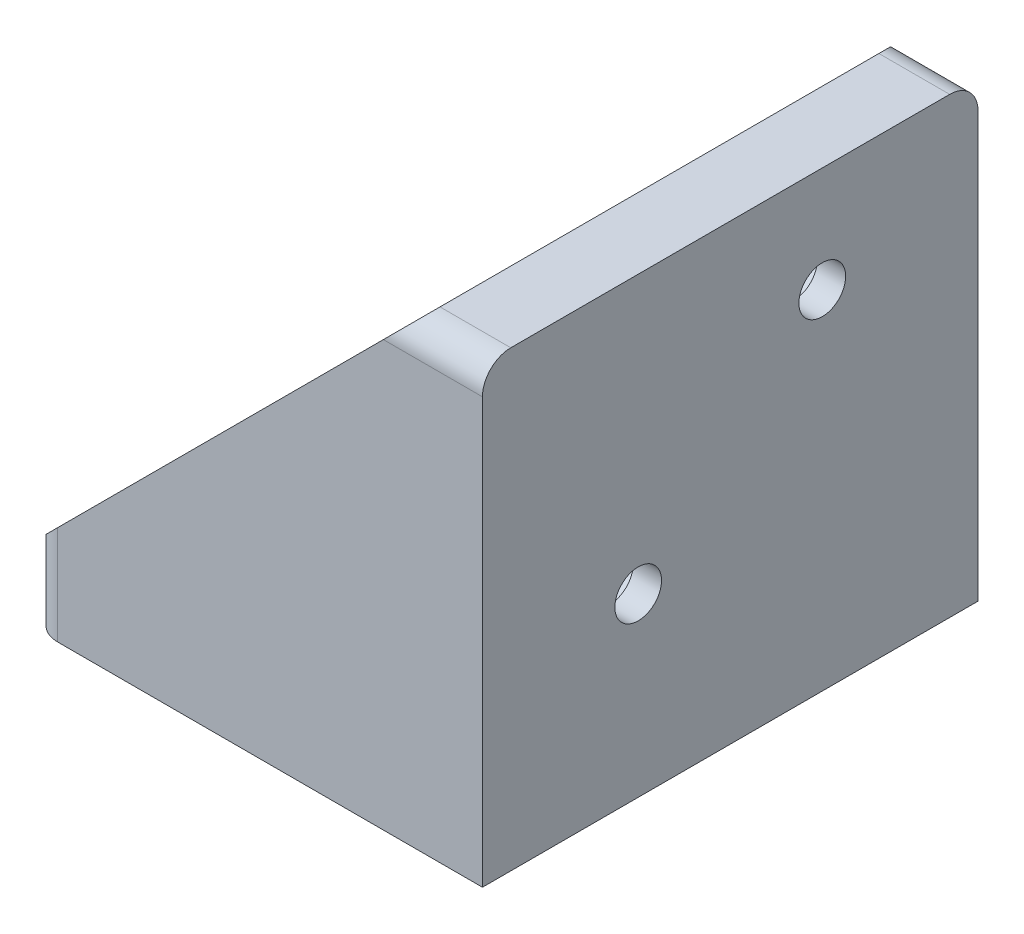
SolidWorks part; units mm, degrees
ref_plane "Спереди" through (0, 0, 0) normal (0, 0, 1) x (1, 0, 0)
ref_plane "Сверху" through (0, 0, 0) normal (0, 1, 0) x (1, 0, 0)
ref_plane "Справа" through (0, 0, 0) normal (1, 0, 0) x (0, 0, -1)
sketch "Эскиз1" plane through (0, 0, 0) normal (0, 0, 1) x (1, 0, 0)
  line L0 (0, 0) -> (-32, 0)
  line L1 (-32, 0) -> (-32, 5)
  line L2 (-32, 5) -> (-5, 5)
  line L3 (-5, 5) -> (-5, 32)
  line L4 (-5, 32) -> (0, 32)
  line L5 (0, 32) -> (0, 0)
  dimension "D1" = 32
  dimension "D2" = 32
  dimension "D3" = 5
  dimension "D4" = 5
extrude "Бобышка-Вытянуть1" add sketch "Эскиз1" along normal blind 35
sketch "Эскиз3" plane through (0, 0, 35) normal (0, 0, 1) x (1, 0, 0)
  line L0 (-32, 5) -> (-5, 32)
rib "Ребро1" sketch "Эскиз3" sketch "Эскиз3" thickness 3 extrusion direction parallel to sketch draft on no parameters "D1"=3
ref_plane "Плоскость4" through (0, 0, 17.5) normal (0, 0, 1) x (1, 0, 0)
mirror "Зеркальное отражение1" about plane through (0, 0, 17.5) normal (0, 0, 1) of "Ребро1"
sketch "Эскиз5" plane through (-5, 0, 0) normal (-1, 0, 0) x (0, 0, 1)
  line L0 (32, 5) -> (3, 32) construction
  line L1 (32, 32) -> (32, 5) construction
  line L2 (24, 8.9842) -> (27, 10.7162)
  line L3 (27, 10.7162) -> (27, 14.1803)
  line L4 (27, 14.1803) -> (24, 15.9124)
  line L5 (24, 15.9124) -> (21, 14.1803)
  line L6 (21, 14.1803) -> (21, 10.7162)
  line L7 (21, 10.7162) -> (24, 8.9842)
  line L8 (3, 5) -> (3, 32) construction
  line L9 (11, 21.0876) -> (14, 22.8197)
  line L10 (14, 22.8197) -> (14, 26.2838)
  line L11 (14, 26.2838) -> (11, 28.0158)
  line L12 (11, 28.0158) -> (8, 26.2838)
  line L13 (8, 26.2838) -> (8, 22.8197)
  line L14 (8, 22.8197) -> (11, 21.0876)
  circle A0 centre (24, 12.4483) radius 3 construction
  circle A1 centre (11, 24.5517) radius 3 construction
  dimension "D1" = 6
  dimension "D2" = 8
  dimension "D3" = 8
extrude "Вырез-Вытянуть1" cut sketch "Эскиз5" against normal blind 3
sketch "Эскиз6" plane through (-2, 0, 0) normal (-1, 0, 0) x (0, 0, 1)
  circle A0 centre (11, 24.5517) radius 3.4641 construction
  circle A1 centre (11, 24.5517) radius 1.65
  circle A2 centre (24, 12.4483) radius 3.4641 construction
  circle A3 centre (24, 12.4483) radius 1.65
  dimension "D1" = 3.3
extrude "Вырез-Вытянуть2" cut sketch "Эскиз6" against normal blind 8
sketch "Эскиз7" plane through (0, 5, 0) normal (0, 1, 0) x (1, 0, 0)
  line L0 (-32, -32) -> (-5, -3) construction
  line L1 (-5, -32) -> (-32, -32) construction
  line L2 (-24.5517, -20.5359) -> (-27.5517, -22.2679)
  line L3 (-27.5517, -22.2679) -> (-27.5517, -25.7321)
  line L4 (-27.5517, -25.7321) -> (-24.5517, -27.4641)
  line L5 (-24.5517, -27.4641) -> (-21.5517, -25.7321)
  line L6 (-21.5517, -25.7321) -> (-21.5517, -22.2679)
  line L7 (-21.5517, -22.2679) -> (-24.5517, -20.5359)
  line L8 (-12.4483, -7.5359) -> (-15.4483, -9.2679)
  line L9 (-15.4483, -9.2679) -> (-15.4483, -12.7321)
  line L10 (-15.4483, -12.7321) -> (-12.4483, -14.4641)
  line L11 (-12.4483, -14.4641) -> (-9.4483, -12.7321)
  line L12 (-9.4483, -12.7321) -> (-9.4483, -9.2679)
  line L13 (-9.4483, -9.2679) -> (-12.4483, -7.5359)
  line L14 (-32, -3) -> (-5, -3) construction
  circle A0 centre (-24.5517, -24) radius 3 construction
  circle A1 centre (-12.4483, -11) radius 3 construction
  dimension "D1" = 6
  dimension "D2" = 8
  dimension "D3" = 8
extrude "Вырез-Вытянуть3" cut sketch "Эскиз7" against normal blind 3
sketch "Эскиз8" plane through (0, 2, 0) normal (0, 1, 0) x (1, 0, 0)
  circle A0 centre (-24.5517, -24) radius 3.4641 construction
  circle A1 centre (-12.4483, -11) radius 3.4641 construction
  circle A2 centre (-24.5517, -24) radius 1.65
  circle A3 centre (-12.4483, -11) radius 1.65
  dimension "D1" = 3.3
  dimension "D2" = 3.3
extrude "Вырез-Вытянуть4" cut sketch "Эскиз8" against normal blind 10
fillet "Скругление1" radius 2 4 edges at (-2.5, 32, 0) (-2.5, 32, 35) (-32, 2.5, 0) (-32, 2.5, 35)
